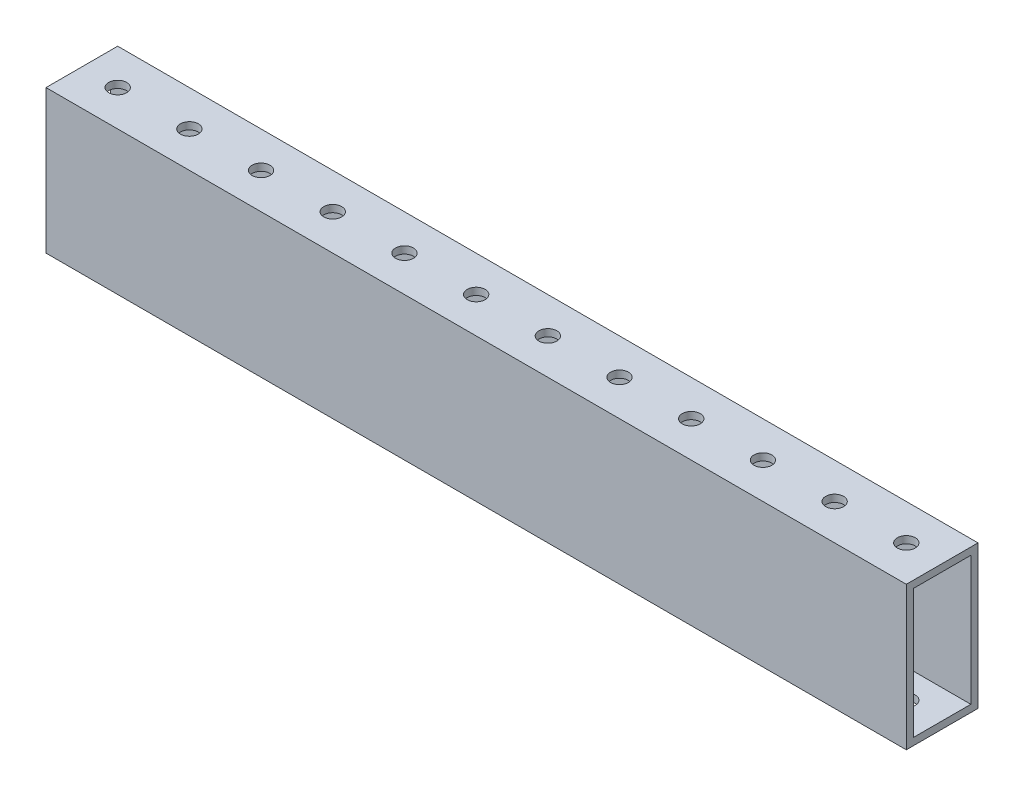
SolidWorks part; units mm, degrees
ref_plane "Front Plane" through (0, 0, 0) normal (0, 0, 1) x (1, 0, 0)
ref_plane "Top Plane" through (0, 0, 0) normal (0, 1, 0) x (1, 0, 0)
ref_plane "Right Plane" through (0, 0, 0) normal (1, 0, 0) x (0, 0, -1)
sketch "Sketch1" plane through (0, 0, 0) normal (1, 0, 0) x (0, 0, -1)
  line L1 (-12.7, -25.4) -> (12.7, -25.4)
  line L2 (-12.7, -25.4) -> (-12.7, 25.4)
  line L3 (-12.7, 25.4) -> (12.7, 25.4)
  line L4 (12.7, -25.4) -> (12.7, 25.4)
  line L5 (-12.7, -25.4) -> (12.7, 25.4) construction
  line L6 (-12.7, 25.4) -> (12.7, -25.4) construction
  line L7 (-10.16, -22.86) -> (10.16, -22.86)
  line L8 (-10.16, -22.86) -> (-10.16, 22.86)
  line L9 (-10.16, 22.86) -> (10.16, 22.86)
  line L10 (10.16, -22.86) -> (10.16, 22.86)
  line L11 (-10.16, -22.86) -> (10.16, 22.86) construction
  line L12 (-10.16, 22.86) -> (10.16, -22.86) construction
  point P0 (0, 0)
  point P6 (0, 0)
  dimension "D1" = 50.8
  dimension "D2" = 25.4
  dimension "D3" = 20.32
  dimension "D4" = 45.72
extrude "Boss-Extrude1" add sketch "Sketch1" along normal blind 304.8
sketch "Sketch2" plane through (0, 25.4, 0) normal (0, 1, 0) x (1, 0, 0)
  line L0 (-1000, 0) -> (49000, 0) construction
  line L1 (0, 12.7) -> (0, -12.7) construction
  line L2 (12.7, 0) -> (38.1, 0) construction
  circle A0 centre (12.7, 0) radius 3.175
  circle A1 centre (38.1, 0) radius 3.175
  circle A2 centre (63.5, 0) radius 3.175
  circle A3 centre (88.9, 0) radius 3.175
  circle A4 centre (114.3, 0) radius 3.175
  circle A5 centre (139.7, 0) radius 3.175
  circle A6 centre (165.1, 0) radius 3.175
  circle A7 centre (190.5, 0) radius 3.175
  circle A8 centre (215.9, 0) radius 3.175
  circle A9 centre (241.3, 0) radius 3.175
  circle A10 centre (266.7, 0) radius 3.175
  circle A11 centre (292.1, 0) radius 3.175
  dimension "D1" = 6.35
  dimension "D2" = 12.7
  dimension "D4" = 25.4
  dimension "D3" = 12
extrude "Cut-Extrude1" cut sketch "Sketch2" against normal blind 304.8
